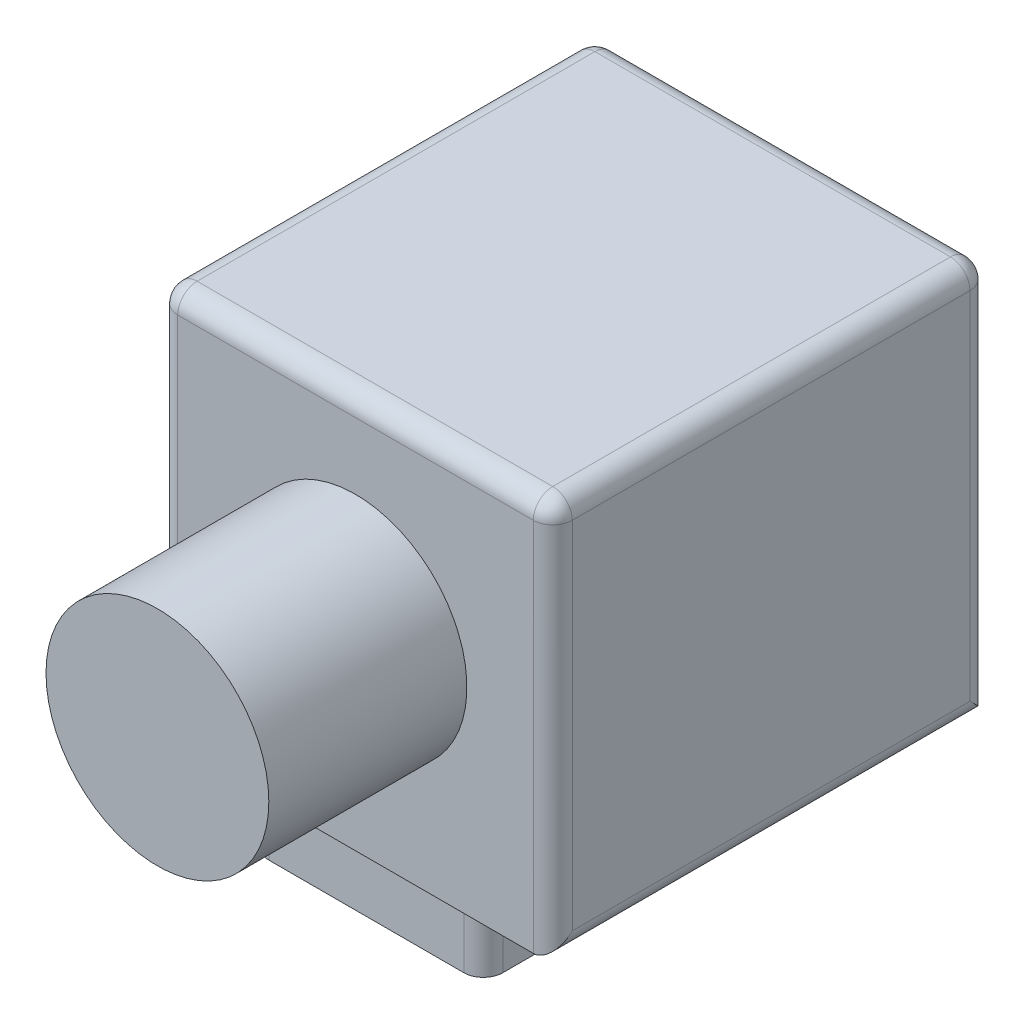
SolidWorks part; units mm, degrees
ref_plane "Front Plane" through (0, 0, 0) normal (0, 0, 1) x (1, 0, 0)
ref_plane "Top Plane" through (0, 0, 0) normal (0, 1, 0) x (1, 0, 0)
ref_plane "Right Plane" through (0, 0, 0) normal (1, 0, 0) x (0, 0, -1)
sketch "Sketch2" plane through (0, 0, 0) normal (0, 1, 0) x (1, 0, 0)
  line L1 (0, 0) -> (50.6, 0)
  line L2 (0, 0) -> (0, 56)
  line L3 (0, 56) -> (50.6, 56)
  line L4 (50.6, 0) -> (50.6, 56)
  dimension "D1" = 56
  dimension "D2" = 50.6
extrude "Boss-Extrude1" add sketch "Sketch2" along normal blind 50.6
sketch "Sketch3" plane through (0, 0, 0) normal (0, -1, 0) x (1, 0, 0)
  line L0 (50.6, 0) -> (0, -56) construction
  line L1 (10.3, -1.4) -> (40.3, -1.4)
  line L2 (10.3, -1.4) -> (10.3, -54.6)
  line L3 (10.3, -54.6) -> (40.3, -54.6)
  line L4 (40.3, -1.4) -> (40.3, -54.6)
  line L5 (0, 0) -> (50.6, -56) construction
  line L6 (25.3, -1.4) -> (25.3, -54.6) construction
  point P12 (25.3, -28)
  point P15 (25.3, -28)
  dimension "D1" = 53.2
  dimension "D2" = 30
extrude "Boss-Extrude2" add sketch "Sketch3" along normal blind 8
sketch "Sketch4" plane through (0, -8, 0) normal (0, -1, 0) x (1, 0, 0)
  line L0 (25.3, -1.4) -> (25.3, -54.6)
  line L1 (40.3, -1.4) -> (10.3, -1.4) construction
  line L2 (10.3, -54.6) -> (40.3, -54.6) construction
  line L3 (50.6, -56) -> (0, -56) construction
  circle A0 centre (25.3, -22) radius 2.765
  circle A1 centre (25.3, -35.25) radius 1.5056
  circle A2 centre (25.3, -48.5) radius 1.5056
  circle A3 centre (25.3, -6.3) radius 1.5056
  dimension "D1" = 7.5
  dimension "D2" = 20.75
  dimension "D3" = 34
  dimension "D4" = 49.7
hole_wizard "Tap Drill for M6x1.0 Tap1" positions "Sketch8" profile "Sketch7" hole size "M6x1.0" standard "Ansi Metric"
sketch "Sketch8" plane through (0, -8, 0) normal (0, -1, 0) x (1, 0, 0)
  point P0 (25.3, -35.25)
  point P1 (25.3, -48.5)
  point P4 (25.3, -6.3)
sketch "Sketch7" plane through (25.3, -8, -35.25) normal (1, 0, 0) x (0, 0, -1)
  line L0 (0, 0) -> (0, 9.0022)
  line L1 (0, 9.0022) -> (2.5, 7.5)
  line L2 (2.5, 7.5) -> (2.5, 0)
  line L5 (2.5, 0) -> (0, 0)
  line L10 (0, 9.0022) -> (-2.5, 7.5) construction
  line L11 (0, -6.35) -> (0, 107.95) construction
  dimension "Hole Dia." = 5
  dimension "Hole Depth" = 7.5
  dimension "Drill Angle" = 118
hole_wizard "Tap Drill for 1/4-20 Tap1" positions "Sketch10" profile "Sketch9" hole size "1/4-20" standard "Ansi Inch"
sketch "Sketch10" plane through (0, -8, 0) normal (0, -1, 0) x (1, 0, 0)
  point P0 (25.3, -22)
sketch "Sketch9" plane through (25.3, -8, -22) normal (1, 0, 0) x (0, 0, -1)
  line L0 (0, 0) -> (0, 9.1538)
  line L1 (0, 9.1538) -> (2.5527, 7.62)
  line L2 (2.5527, 7.62) -> (2.5527, 0)
  line L5 (2.5527, 0) -> (0, 0)
  line L10 (0, 9.1538) -> (-2.5527, 7.62) construction
  line L11 (0, -6.35) -> (0, 107.95) construction
  dimension "Hole Dia." = 5.1054
  dimension "Hole Depth" = 7.62
  dimension "Drill Angle" = 118
sketch "Sketch11" plane through (0, 0, 0) normal (0, 0, 1) x (1, 0, 0)
  line L0 (0, 50.6) -> (50.6, 0) construction
  circle A0 centre (25.3, 25.3) radius 14.2875
  dimension "D1" = 28.575
extrude "Boss-Extrude3" add sketch "Sketch11" along normal blind 25.4
fillet "Fillet1" radius 2.5 14 edges at (0, 25.3, -56) (50.6, 25.3, -56) (0, 25.3, 0) (50.6, 25.3, 0) (25.3, 50.6, 0) (25.3, 50.6, -56) (40.3, -4, -54.6) (10.3, -4, -54.6) (40.3, -4, -1.4) (10.3, -4, -1.4) (0, 0, -28) (50.6, 0, -28) (0, 50.6, -28) (50.6, 50.6, -28)
sketch "Sketch12" plane through (50.6, 0, 0) normal (1, 0, 0) x (0, 0, -1)
  line L0 (53.5, 48.1) -> (2.5, 2.5) construction
  point P4 (28, 25.3)
ref_plane "Plane1" through (0, 25.3, 0) normal (0, 1, 0) x (-1, 0, 0)
sketch "Sketch13" [suppressed] plane through (0, 50.6, 0) normal (0, 1, 0) x (1, 0, 0)
  line L0 (2.5, 53.5) -> (48.1, 2.5) construction
  point P4 (25.3, 28)
sketch3d "3DSketch1"
  line L1 (-90.3853, 25.3, -28) -> (140.9853, 25.3, -28) construction
  line L2 (25.3, 145.3091, -28) -> (25.3, -94.7091, -28) construction
  point P4 (25.3, 25.3, -28)
